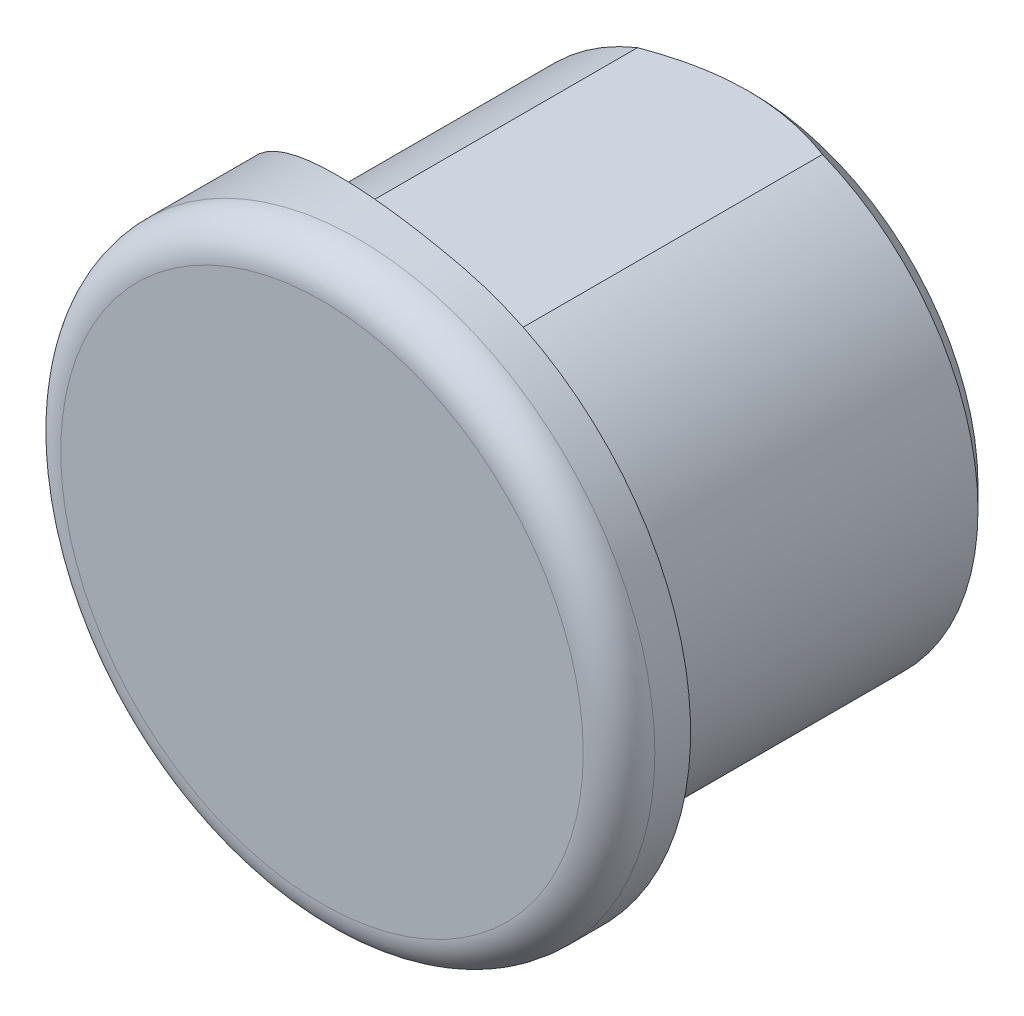
SolidWorks part; units mm, degrees
ref_plane "Plan de face" through (0, 0, 0) normal (0, 0, 1) x (1, 0, 0)
ref_plane "Plan de dessus" through (0, 0, 0) normal (0, 1, 0) x (1, 0, 0)
ref_plane "Plan de droite" through (0, 0, 0) normal (1, 0, 0) x (0, 0, -1)
sketch "Esquisse1" plane through (0, 0, 0) normal (0, 0, 1) x (1, 0, 0)
  circle A0 centre (-38, 67) radius 3.465
  dimension "D1" = 6.93
extrude "Boss.-Extru.1" add sketch "Esquisse1" against normal blind 5
sketch "Esquisse2" plane through (0, 0, 0) normal (0, 0, 1) x (1, 0, 0)
  circle A0 centre (-38, 67) radius 4.15
  dimension "D1" = 8.3
extrude "Boss.-Extru.2" add sketch "Esquisse2" along normal blind 1
fillet "Congé1" radius 0.5 1 edges at (-33.85, 67, 1)
ref_plane "Plan1" through (-41.465, 0, 0) normal (-1, 0, 0) x (0, 0, 1)
ref_plane "Plan2" through (0, 71.15, 0) normal (0, 1, 0) x (1, 0, 0)
sketch "Esquisse4" plane through (29.785, 71.15, 0) normal (0, -1, 0) x (0, 0, 1)
  line L0 (-5, 67.785) -> (1, 67.785) construction
  line L1 (-5, 71.25) -> (-5, 64.32) construction
  line L2 (1, 64.135) -> (1, 71.435) construction
  line L3 (-5, 66.82) -> (0, 66.82) construction
  line L4 (0, 71.25) -> (0, 64.32) construction
  line L5 (0, 71.935) -> (-1.8488, 71.935)
  line L6 (0, 71.935) -> (0, 66.82)
  line L8 (-5, 64.32) -> (0, 64.32) construction
  arc A0 (0, 66.82) -> (-1.8488, 71.935) centre (-8, 66.82) ccw
  dimension "D2" = 8
  dimension "D1" = 2.5
extrude "Boss.-Extru.3" add sketch "Esquisse4" along normal blind 9 and the other way blind 2
sketch "Esquisse5" plane through (0, 0, 1) normal (0, 0, 1) x (1, 0, 0)
  line L0 (-37.035, 62.9638) -> (-36.6285, 58.673)
  line L1 (-36.6285, 58.673) -> (-43.8082, 59.4661)
  line L2 (-43.8082, 59.4661) -> (-42.997, 73.4865)
  line L3 (-42.997, 73.4865) -> (-36.6285, 73.5245)
  line L4 (-36.6285, 73.5245) -> (-37.035, 71.0362)
  arc A0 (-42.15, 67) -> (-37.035, 62.9638) centre (-38, 67) ccw construction
  arc A1 (-42.15, 67) -> (-37.035, 62.9638) centre (-38, 67) ccw
  arc A2 (-37.035, 71.0362) -> (-42.15, 67) centre (-38, 67) ccw construction
  arc A3 (-37.035, 71.0362) -> (-42.15, 67) centre (-38, 67) ccw
extrude "Enlèv. mat.-Extru.1" cut sketch "Esquisse5" against normal blind 4
chamfer "Chanfrein1" distance 0.3 angle 45 1 edges at (-34.535, 67, -5)
sketch "Esquisse7" plane through (0, 0, -5) normal (0, 0, -1) x (-1, 0, 0)
  line L0 (36.7077, 70.215) -> (39.2923, 70.215)
  arc A0 (37.035, 70.3279) -> (37.035, 63.6721) centre (38, 67) ccw construction
  circle A1 centre (38, 67) radius 3.465 construction
  arc A2 (37.035, 63.6721) -> (37.035, 70.3279) centre (38, 67) ccw construction
  arc A3 (39.2923, 70.215) -> (37.035, 70.3279) centre (38, 67) ccw
  arc A4 (37.035, 70.3279) -> (36.7077, 70.215) centre (38, 67) ccw
  point P2 (38, 70.465)
  dimension "D1" = 0.25
extrude "Enlèv. mat.-Extru.2" cut sketch "Esquisse7" against normal up to surface (4.6749 mm away)
